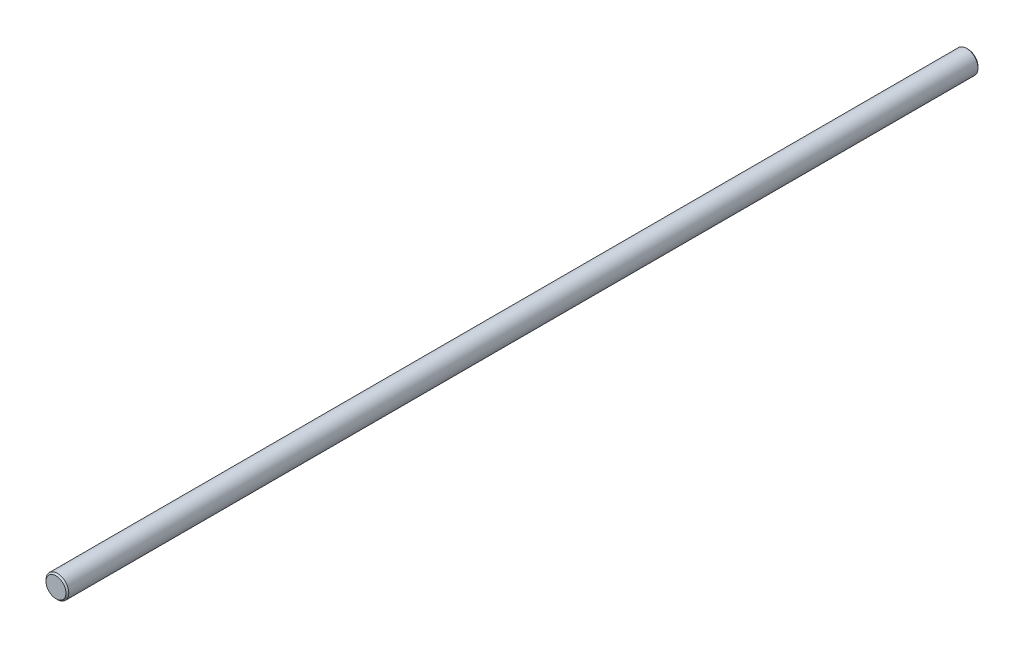
SolidWorks part; units mm, degrees
material "1023 Arkusz stali węglowej (SS)"
ref_plane "Płaszczyzna przednia" through (0, 0, 0) normal (0, 0, 1) x (1, 0, 0)
ref_plane "Płaszczyzna górna" through (0, 0, 0) normal (0, 1, 0) x (1, 0, 0)
ref_plane "Płaszczyzna prawa" through (0, 0, 0) normal (1, 0, 0) x (0, 0, -1)
sketch "Szkic1" plane through (0, 0, 0) normal (0, 0, 1) x (1, 0, 0)
  circle A0 centre (0, 0) radius 4
  dimension "D1" = 8
extrude "Dodanie-wyciągnięcie1" add sketch "Szkic1" along normal blind 320
chamfer "Sfazowanie1" distance 0.5 angle 45 2 edges at (4, 0, 320) (4, 0, 0)
